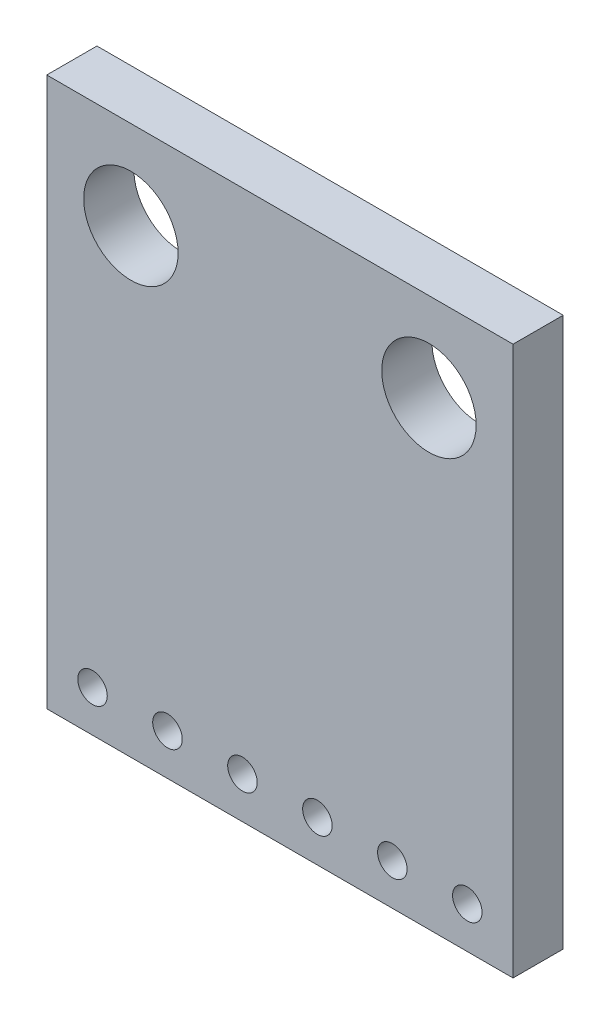
SolidWorks part; units mm, degrees
ref_plane "Front Plane" through (0, 0, 0) normal (0, 0, 1) x (1, 0, 0)
ref_plane "Top Plane" through (0, 0, 0) normal (0, 1, 0) x (1, 0, 0)
ref_plane "Right Plane" through (0, 0, 0) normal (1, 0, 0) x (0, 0, -1)
sketch "Sketch1" plane through (0, 0, 0) normal (0, 0, 1) x (1, 0, 0)
  line L1 (-7.9, 9.3) -> (7.9, 9.3)
  line L2 (-7.9, 9.3) -> (-7.9, -9.3)
  line L3 (-7.9, -9.3) -> (7.9, -9.3)
  line L4 (7.9, 9.3) -> (7.9, -9.3)
  line L5 (0, -9.3) -> (0, 9.3) construction
  line L6 (-7.9, 0) -> (7.9, 0) construction
  circle A0 centre (-5.05, 6.3) radius 1.6
  circle A1 centre (5.05, 6.3) radius 1.6
  circle A2 centre (-6.35, -7.9) radius 0.5
  circle A3 centre (-3.81, -7.9) radius 0.5
  circle A4 centre (-1.27, -7.9) radius 0.5
  circle A5 centre (1.27, -7.9) radius 0.5
  circle A6 centre (3.81, -7.9) radius 0.5
  circle A7 centre (6.35, -7.9) radius 0.5
  point P0 (0, 0)
  point P11 (0, 0)
  dimension "D3" = 3.2
  dimension "D4" = 10.1
  dimension "D5" = 5.05
  dimension "D6" = 3
  dimension "D7" = 1
  dimension "D8" = 1.4
  dimension "D10" = 2.54
  dimension "D1" = 15.8
  dimension "D2" = 18.6
  dimension "D9" = 6
extrude "Boss-Extrude1" add sketch "Sketch1" along normal blind 1.7
